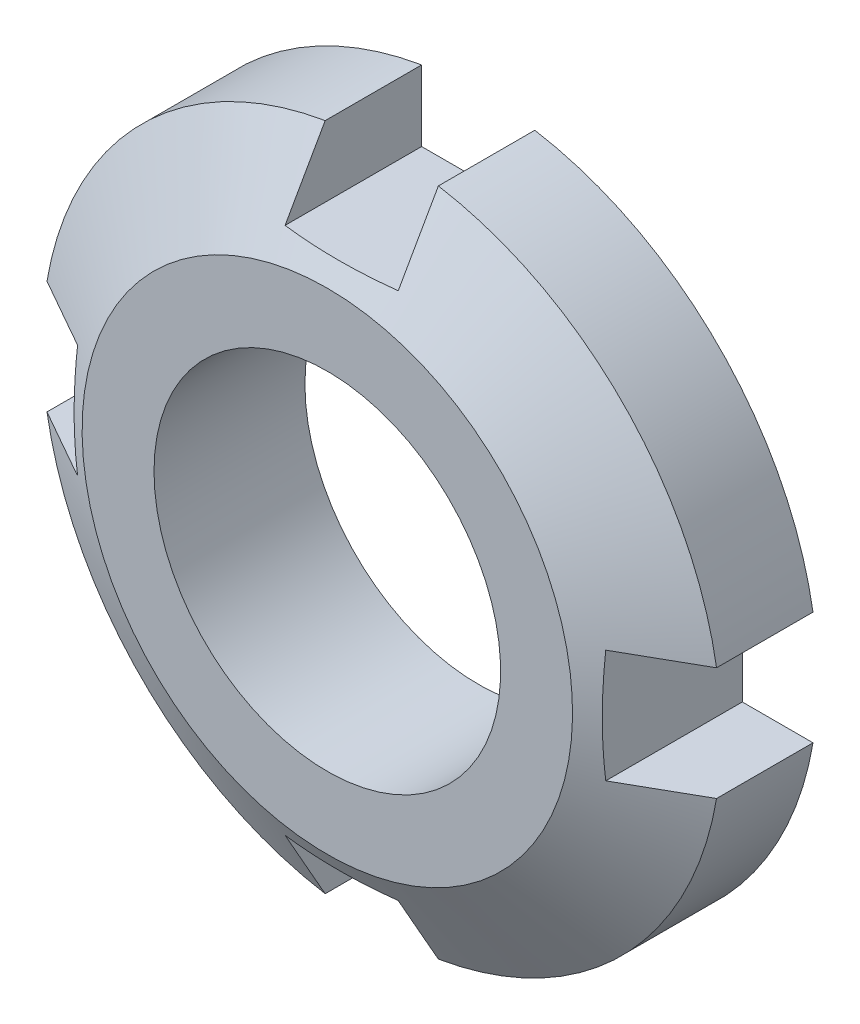
SolidWorks part; units mm, degrees
ref_plane "Front Plane" through (0, 0, 0) normal (0, 0, 1) x (1, 0, 0)
ref_plane "Top Plane" through (0, 0, 0) normal (0, 1, 0) x (1, 0, 0)
ref_plane "Right Plane" through (0, 0, 0) normal (1, 0, 0) x (0, 0, -1)
sketch "Sketch1" plane through (0, 0, 0) normal (1, 0, 0) x (0, 0, -1)
  line L0 (0, 9) -> (-2.5566, 9)
  line L1 (-2.5566, 9) -> (-4, 6.5)
  line L2 (-4, 6.5) -> (-4, 0)
  line L3 (-4, 0) -> (0, 0)
  line L4 (0, 0) -> (0, 9)
  line L5 (0, 0) -> (-4, 0) construction
  dimension "FIX_1" = 30
  dimension "B" = 4
  dimension "D2." = 13
revolve "Revolve1" add sketch "Sketch1" angle 360 about L5
hole_wizard "Tap1" positions "Sketch3" profile "Sketch2" hole size "M10x1.25" standard "JIS" end condition through all
sketch "Sketch3" plane through (0, 0, 0) normal (0, 0, -1) x (-1, 0, 0)
  point P0 (0, 0)
cosmetic thread "Thread1" parameters "M"=10
sketch "Sketch2" plane through (0, 0, 0) normal (1, 0, 0) x (0, 1, 0)
  line L0 (0, 0) -> (0, 4)
  line L1 (0, 4) -> (4.594, 4)
  line L2 (4.594, 4) -> (4.594, 0)
  line L5 (4.594, 0) -> (0, 0)
  line L11 (0, 0) -> (0, 4) construction
  dimension "STD_1" = 9.188
  dimension "Thru Hole Depth" = 4
sketch "Sketch4" plane through (0, 0, 0) normal (0, 0, 1) x (1, 0, 0)
  line L0 (-9, 0) -> (9, 0) construction
  line L1 (-1.5, 9) -> (1.5, 9)
  line L2 (-1.5, 9) -> (-1.5, 7)
  line L3 (-1.5, 7) -> (1.5, 7)
  line L4 (1.5, 9) -> (1.5, 7)
  line L5 (-9, 1.5) -> (-7, 1.5)
  line L6 (-9, 1.5) -> (-9, -1.5)
  line L7 (-9, -1.5) -> (-7, -1.5)
  line L8 (-7, 1.5) -> (-7, -1.5)
  line L9 (9, 1.5) -> (7, 1.5)
  line L10 (9, 1.5) -> (9, -1.5)
  line L11 (9, -1.5) -> (7, -1.5)
  line L12 (7, 1.5) -> (7, -1.5)
  line L13 (1.5, -9) -> (-1.5, -9)
  line L14 (1.5, -9) -> (1.5, -7)
  line L15 (1.5, -7) -> (-1.5, -7)
  line L16 (-1.5, -9) -> (-1.5, -7)
  line L18 (0, 9) -> (0, -9) construction
  dimension "S" = 3
  dimension "T" = 2
  dimension "D_s" = 14
extrude "Cut-Extrude1" cut sketch "Sketch4" along normal through all
